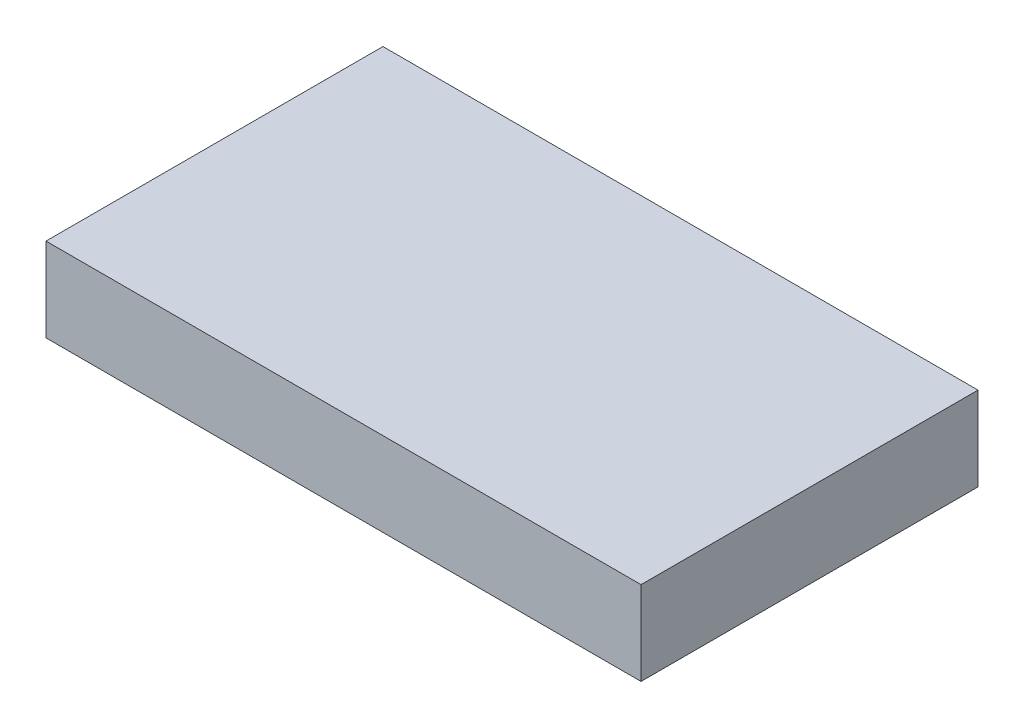
SolidWorks part; units mm, degrees
ref_plane "Front Plane" through (0, 0, 0) normal (0, 0, 1) x (1, 0, 0)
ref_plane "Top Plane" through (0, 0, 0) normal (0, 1, 0) x (1, 0, 0)
ref_plane "Right Plane" through (0, 0, 0) normal (1, 0, 0) x (0, 0, -1)
sketch "Sketch1" plane through (0, 0, 0) normal (0, 1, 0) x (1, 0, 0)
  line L1 (-37.325, -21.135) -> (37.325, -21.135)
  line L2 (-37.325, -21.135) -> (-37.325, 21.135)
  line L3 (-37.325, 21.135) -> (37.325, 21.135)
  line L4 (37.325, -21.135) -> (37.325, 21.135)
  line L5 (-37.325, -21.135) -> (37.325, 21.135) construction
  line L6 (-37.325, 21.135) -> (37.325, -21.135) construction
  point P0 (0, 0)
  dimension "D1" = 74.65
  dimension "D2" = 42.27
extrude "Boss-Extrude1" add sketch "Sketch1" along normal blind 10.52
sketch "Sketch2" plane through (0, 10.52, 0) normal (0, 1, 0) x (1, 0, 0)
  line L0 (37.325, 0) -> (-37.325, 0)
  line L1 (-37.325, 21.135) -> (-37.325, -21.135) construction
  text T0 "AM116A ESC"
  point P6 (0, 0)
